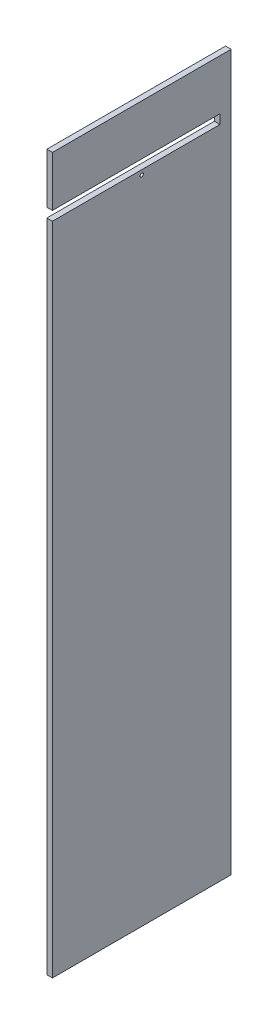
SolidWorks part; units mm, degrees
ref_plane "Front Plane" through (0, 0, 0) normal (0, 0, 1) x (1, 0, 0)
ref_plane "Top Plane" through (0, 0, 0) normal (0, 1, 0) x (1, 0, 0)
ref_plane "Right Plane" through (0, 0, 0) normal (1, 0, 0) x (0, 0, -1)
sketch "Sketch1" plane through (0, 0, 0) normal (0, 1, 0) x (1, 0, 0)
  line L1 (0, 0) -> (4.7625, 0)
  line L2 (0, 0) -> (0, 152.4)
  line L3 (0, 152.4) -> (4.7625, 152.4)
  line L4 (4.7625, 0) -> (4.7625, 152.4)
  dimension "D1" = 152.4
  dimension "D2" = 4.7625
extrude "Boss-Extrude1" add sketch "Sketch1" along normal blind 609.6
sketch "Sketch2" plane through (4.7625, 0, 0) normal (1, 0, 0) x (0, 0, -1)
  line L1 (0, 558.8) -> (142.875, 558.8)
  line L2 (0, 558.8) -> (0, 566.7375)
  line L3 (0, 566.7375) -> (142.875, 566.7375)
  line L4 (142.875, 558.8) -> (142.875, 566.7375)
extrude "Cut-Extrude1" cut sketch "Sketch2" against normal through all
hole_wizard "#4 Clearance Hole1" positions "Sketch9" profile "Sketch10" hole size "#4" standard "ANSI Inch" end condition through all
sketch "Sketch9" plane through (4.7625, 0, 0) normal (1, 0, 0) x (0, 0, -1)
  line L0 (147.6375, 550.8625) -> (4.7625, 558.8) construction
  line L1 (0, 558.8) -> (142.875, 558.8) construction
  point P5 (76.2, 554.8312)
sketch "Sketch10" plane through (4.7625, 554.8312, -76.2) normal (0, 1, 0) x (0, 0, -1)
  line L0 (0, 0) -> (0, 4.7625)
  line L1 (0, 4.7625) -> (1.4732, 4.7625)
  line L2 (1.4732, 4.7625) -> (1.4732, 0)
  line L5 (1.4732, 0) -> (0, 0)
  line L11 (0, -6.35) -> (0, 107.95) construction
  dimension "Thru Hole Dia." = 2.9464
  dimension "Thru Hole Depth" = 4.7625
